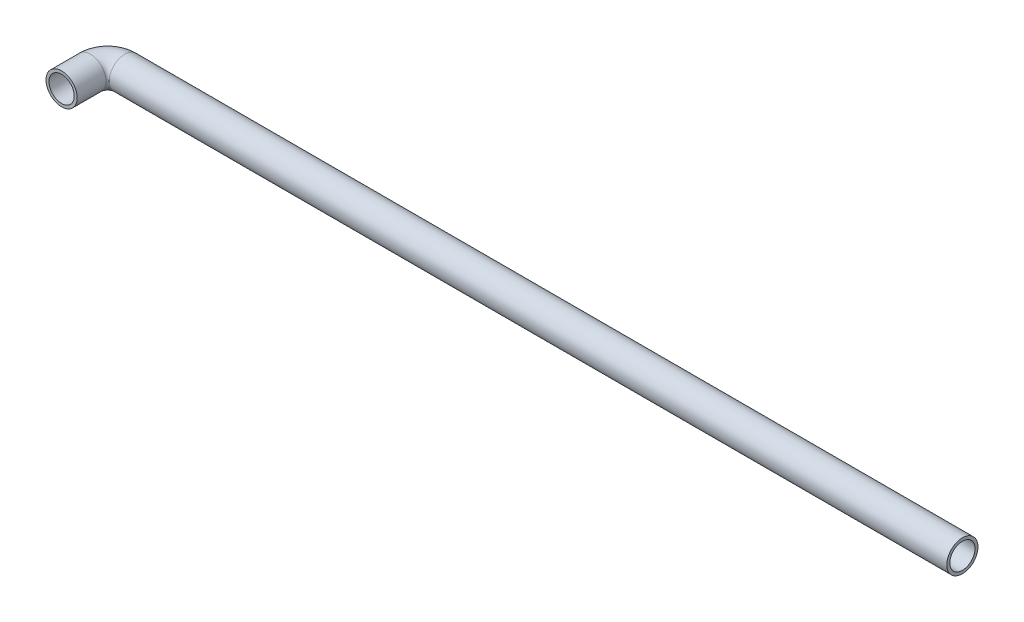
SolidWorks part; units mm, degrees
ref_plane "Front Plane" through (0, 0, 0) normal (0, 0, 1) x (1, 0, 0)
ref_plane "Top Plane" through (0, 0, 0) normal (0, 1, 0) x (1, 0, 0)
ref_plane "Right Plane" through (0, 0, 0) normal (1, 0, 0) x (0, 0, -1)
sketch "Sketch1" plane through (0, 0, 0) normal (0, 0, 1) x (1, 0, 0)
  circle A0 centre (0, 0) radius 5.5562
  circle A1 centre (0, 0) radius 6.858
  dimension "D1" = 13.716
  dimension "D2" = 11.1125
sketch "Sketch2" plane through (0, 0, 0) normal (0, 1, 0) x (1, 0, 0)
  line L0 (0, 0) -> (0, 12.7)
  line L1 (7.5408, 20.2408) -> (375.8408, 20.2408)
  arc A0 (0, 12.7) -> (7.5408, 20.2408) centre (7.5408, 12.7) cw
  dimension "D1" = 12.7
  dimension "D2" = 368.3
sweep "Sweep1" add profiles "Sketch1" path "Sketch2"
